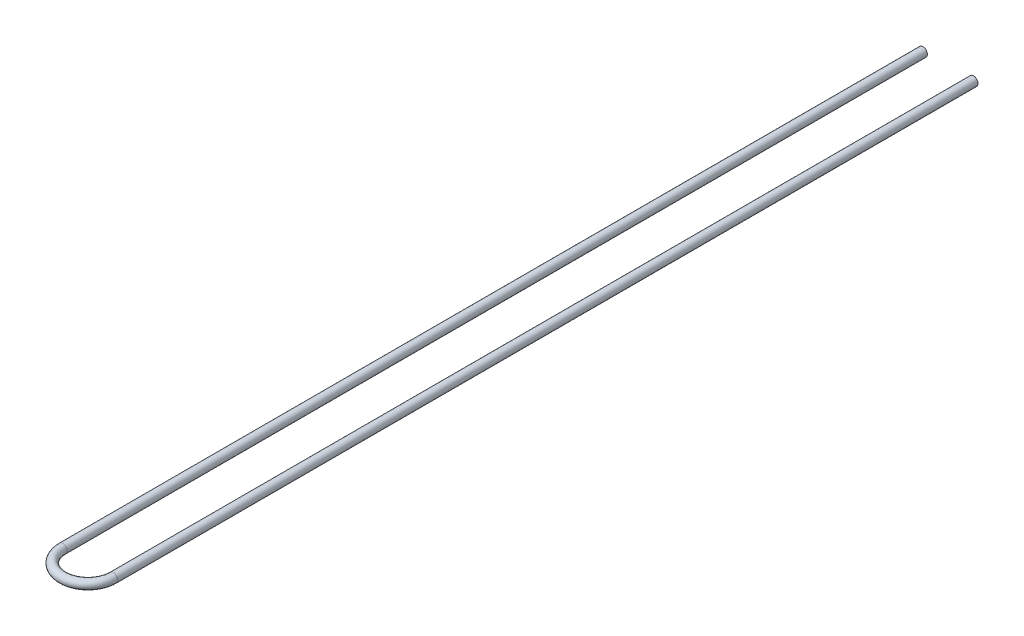
SolidWorks part; units mm, degrees
ref_plane "Front Plane" through (0, 0, 0) normal (0, 0, 1) x (1, 0, 0)
ref_plane "Top Plane" through (0, 0, 0) normal (0, 1, 0) x (1, 0, 0)
ref_plane "Right Plane" through (0, 0, 0) normal (1, 0, 0) x (0, 0, -1)
sketch "Sketch1" plane through (0, 0, 0) normal (0, 1, 0) x (1, 0, 0)
  line L0 (85.85, -300) -> (85.85, -2440)
  line L2 (-40, -300) -> (-40, -2440)
  arc A0 (-40, -2440) -> (85.85, -2440) centre (22.925, -2440) ccw
  dimension "D1" = 2140
  dimension "D2" = 125.85
ref_plane "Plane1" through (85.85, 0, 300) normal (0, 0, -1) x (-1, 0, 0)
sketch "Sketch2" plane through (85.85, 0, 300) normal (0, 0, -1) x (-1, 0, 0)
  circle A0 centre (0, 0) radius 9.95
  circle A1 centre (0, 0) radius 11.1
  dimension "D1" = 22.2
  dimension "D2" = 19.9
sweep "Sweep1" add profiles "Sketch2" path "Sketch1"
